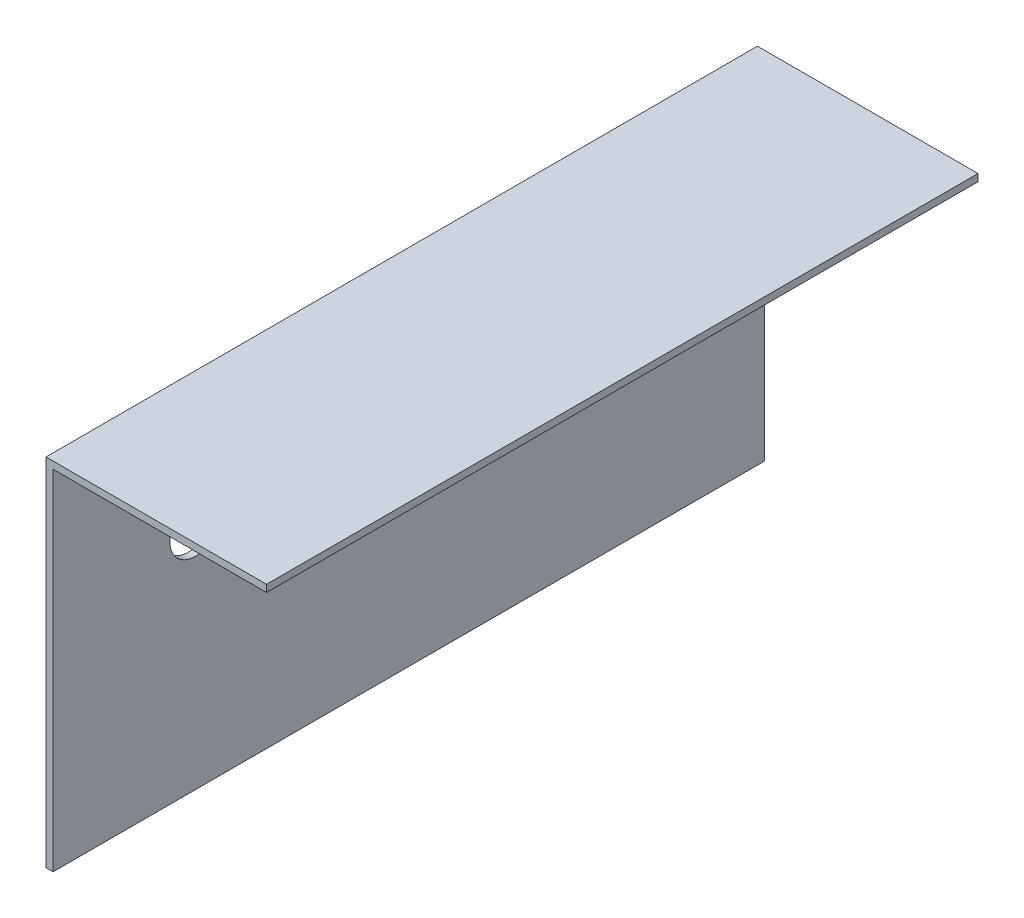
SolidWorks part; units mm, degrees
material "AISI 1020"
ref_plane "Front" through (0, 0, 0) normal (0, 0, 1) x (1, 0, 0)
ref_plane "Top" through (0, 0, 0) normal (0, 1, 0) x (1, 0, 0)
ref_plane "Right" through (0, 0, 0) normal (1, 0, 0) x (0, 0, -1)
sketch "Эскиз1" plane through (0, 0, 0) normal (1, 0, 0) x (0, 0, -1)
  line L1 (-56.9338, 22.5) -> (-6.9338, 22.5)
  line L2 (-56.9338, 22.5) -> (-56.9338, -2.5)
  line L3 (-56.9338, -2.5) -> (-6.9338, -2.5)
  line L4 (-6.9338, 22.5) -> (-6.9338, -2.5)
  dimension "D1" = 50
  dimension "D2" = 25
extrude "Бобышка-Вытянуть1" add sketch "Эскиз1" along normal blind 0.5
sketch "Эскиз2" plane through (0.5, 0, 0) normal (1, 0, 0) x (0, 0, -1)
  line L0 (-6.9338, -2.5) -> (-6.9338, 22.5) construction
  line L1 (-56.9338, 22.5) -> (-6.9338, 22.5)
  line L2 (-56.9338, 22.5) -> (-56.9338, 22)
  line L3 (-56.9338, 22) -> (-6.9338, 22)
  line L4 (-6.9338, 22.5) -> (-6.9338, 22)
  dimension "D1" = 0.5
extrude "Бобышка-Вытянуть2" add sketch "Эскиз2" along normal blind 15
hole_wizard "Диаметр отверстия Ø3.6 (3.6)1" positions "Эскиз4" profile "Эскиз3" hole size "Ø3.6" standard "Ansi Metric"
sketch "Эскиз4" plane through (0, 0, 0) normal (-1, 0, 0) x (0, 0, 1)
  line L0 (6.9338, 22.5) -> (56.9338, 22.5) construction
  line L1 (6.9338, -2.5) -> (6.9338, 22.5) construction
  line L2 (56.9338, 22.5) -> (56.9338, -2.5) construction
  point P0 (16.9338, 13.5)
  point P2 (46.9338, 13.5)
  point P3 (16.9338, 13.5)
  dimension "D1" = 9
  dimension "D2" = 10
  dimension "D3" = 10
sketch "Эскиз3" plane through (0, 13.5, 16.9338) normal (0, 1, 0) x (0, 0, 1)
  line L0 (0, 0) -> (0, 11.0815)
  line L1 (0, 11.0815) -> (1.8, 10)
  line L2 (1.8, 10) -> (1.8, 0)
  line L5 (1.8, 0) -> (0, 0)
  line L10 (0, 11.0815) -> (-1.8, 10) construction
  line L11 (0, -6.35) -> (0, 107.95) construction
  dimension "Диаметр отверстия" = 3.6
  dimension "Глубина отверстия" = 10
  dimension "Угол заточки сверла" = 118
